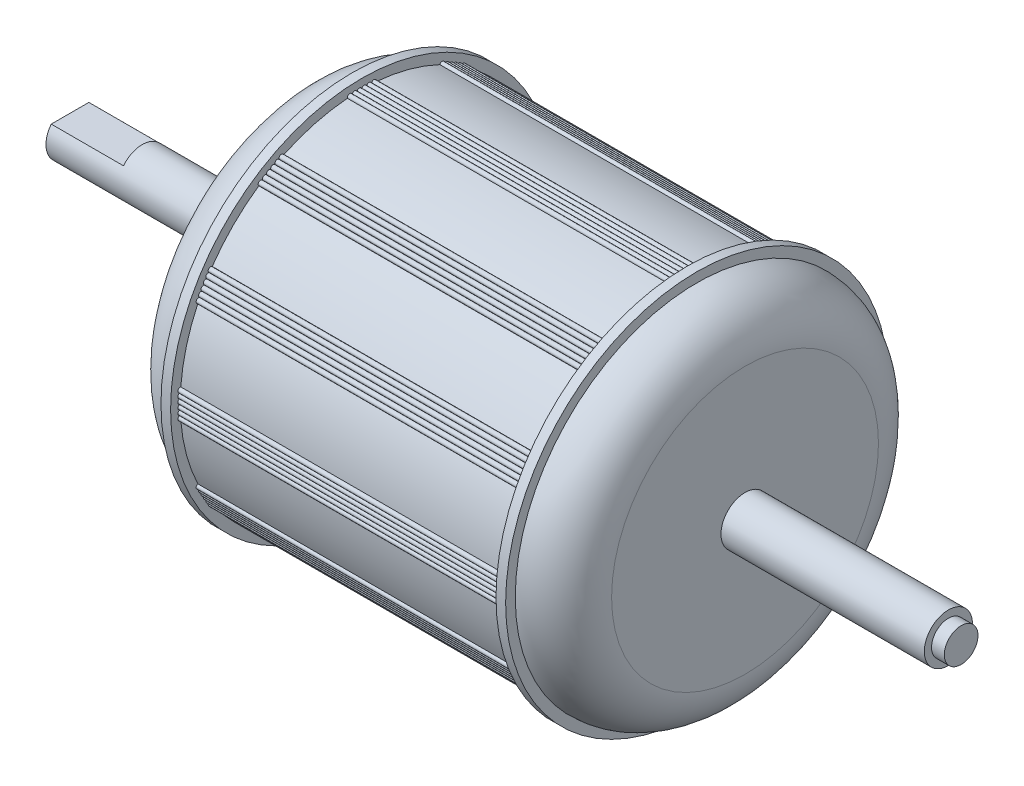
SolidWorks part; units mm, degrees
ref_plane "Front Plane" through (0, 0, 0) normal (0, 0, 1) x (1, 0, 0)
ref_plane "Top Plane" through (0, 0, 0) normal (0, 1, 0) x (1, 0, 0)
ref_plane "Right Plane" through (0, 0, 0) normal (1, 0, 0) x (0, 0, -1)
sketch "Sketch1" plane through (0, 0, 0) normal (0, 0, 1) x (1, 0, 0)
  line L0 (0, 0) -> (185.01, 0) construction
  line L1 (185.01, 0) -> (185.01, 3.5)
  line L2 (185.01, 3.5) -> (182.36, 3.5)
  line L3 (182.36, 3.5) -> (182.36, 5)
  line L4 (182.36, 5) -> (140.14, 5)
  line L5 (0, 0) -> (0, 5)
  line L6 (0, 5) -> (48.58, 5)
  line L7 (48.58, 5) -> (48.58, 27.705)
  line L8 (58.58, 37.705) -> (58.58, 39.705)
  line L9 (58.58, 39.705) -> (60.58, 39.705)
  line L10 (60.58, 39.705) -> (60.58, 37.71)
  line L11 (60.58, 37.71) -> (128.14, 37.71)
  line L13 (128.14, 39.705) -> (128.14, 37.71)
  line L14 (130.14, 39.705) -> (128.14, 39.705)
  line L15 (130.14, 37.705) -> (130.14, 39.705)
  line L16 (140.14, 5) -> (140.14, 27.705)
  line L17 (185.01, 0) -> (0, 0)
  arc A0 (48.58, 27.705) -> (58.58, 37.705) centre (58.58, 27.705) cw
  arc A1 (140.14, 27.705) -> (130.14, 37.705) centre (130.14, 27.705) ccw
  point P22 (94.36, 37.71)
  dimension "D6" = 10
  dimension "D1" = 185.01
  dimension "D2" = 7
  dimension "D3" = 2.65
  dimension "D4" = 10
  dimension "D5" = 48.58
  dimension "D7" = 79.41
  dimension "D8" = 2
  dimension "D9" = 37.71
  dimension "D10" = 12
  dimension "D11" = 91.56
  dimension "D12" = 67.56
revolve "Revolve1" add sketch "Sketch1" angle 360 about L17
sketch "Sketch2" plane through (0, 0, 0) normal (-1, 0, 0) x (0, 0, 1)
  line L0 (-3.905, 3.1227) -> (-3.905, 3.12)
  line L1 (-3.905, 3.12) -> (3.905, 3.12)
  line L2 (3.905, 3.12) -> (3.905, 3.1227)
  circle A0 centre (0, 0) radius 5 construction
  circle A1 centre (0, 0) radius 5 construction
  arc A2 (3.905, 3.1227) -> (-3.905, 3.1227) centre (0, 0) ccw
  point P4 (0, 3.12)
  point P9 (0, 5)
  dimension "D1" = 7.81
  dimension "D2" = 1.88
extrude "Cut-Extrude1" cut sketch "Sketch2" against normal blind 15
sketch "Sketch3" plane through (60.58, 0, 0) normal (1, 0, 0) x (0, 0, -1)
  line L0 (-3, 37.5905) -> (-3, 34.71)
  line L1 (3, 37.5905) -> (3, 34.71)
  line L2 (16.1972, 34.0543) -> (14.7569, 31.5597)
  line L3 (21.3933, 31.0543) -> (19.9531, 28.5597)
  line L4 (31.0543, 21.3933) -> (28.5597, 19.9531)
  line L5 (34.0543, 16.1972) -> (31.5597, 14.7569)
  line L6 (37.5905, 3) -> (34.71, 3)
  line L7 (37.5905, -3) -> (34.71, -3)
  line L8 (34.0543, -16.1972) -> (31.5597, -14.7569)
  line L9 (31.0543, -21.3933) -> (28.5597, -19.9531)
  line L10 (21.3933, -31.0543) -> (19.9531, -28.5597)
  line L11 (16.1972, -34.0543) -> (14.7569, -31.5597)
  line L12 (3, -37.5905) -> (3, -34.71)
  line L13 (-3, -37.5905) -> (-3, -34.71)
  line L14 (-16.1972, -34.0543) -> (-14.7569, -31.5597)
  line L15 (-21.3933, -31.0543) -> (-19.9531, -28.5597)
  line L16 (-31.0543, -21.3933) -> (-28.5597, -19.9531)
  line L17 (-34.0543, -16.1972) -> (-31.5597, -14.7569)
  line L18 (-37.5905, -3) -> (-34.71, -3)
  line L19 (-37.5905, 3) -> (-34.71, 3)
  line L20 (-34.0543, 16.1972) -> (-31.5597, 14.7569)
  line L21 (-31.0543, 21.3933) -> (-28.5597, 19.9531)
  line L22 (-21.3933, 31.0543) -> (-19.9531, 28.5597)
  line L23 (-16.1972, 34.0543) -> (-14.7569, 31.5597)
  circle A0 centre (0, 0) radius 37.71 construction
  arc A2 (3, 37.5905) -> (-3, 37.5905) centre (0, 0) ccw
  arc A3 (-3, 34.71) -> (3, 34.71) centre (0, 34.71) ccw
  arc A4 (21.3933, 31.0543) -> (16.1972, 34.0543) centre (0, 0) ccw
  arc A5 (14.7569, 31.5597) -> (19.9531, 28.5597) centre (17.355, 30.0597) ccw
  arc A6 (34.0543, 16.1972) -> (31.0543, 21.3933) centre (0, 0) ccw
  arc A7 (28.5597, 19.9531) -> (31.5597, 14.7569) centre (30.0597, 17.355) ccw
  arc A8 (37.5905, -3) -> (37.5905, 3) centre (0, 0) ccw
  arc A9 (34.71, 3) -> (34.71, -3) centre (34.71, 0) ccw
  arc A10 (31.0543, -21.3933) -> (34.0543, -16.1972) centre (0, 0) ccw
  arc A11 (31.5597, -14.7569) -> (28.5597, -19.9531) centre (30.0597, -17.355) ccw
  arc A12 (16.1972, -34.0543) -> (21.3933, -31.0543) centre (0, 0) ccw
  arc A13 (19.9531, -28.5597) -> (14.7569, -31.5597) centre (17.355, -30.0597) ccw
  arc A14 (-3, -37.5905) -> (3, -37.5905) centre (0, 0) ccw
  arc A15 (3, -34.71) -> (-3, -34.71) centre (0, -34.71) ccw
  arc A16 (-21.3933, -31.0543) -> (-16.1972, -34.0543) centre (0, 0) ccw
  arc A17 (-14.7569, -31.5597) -> (-19.9531, -28.5597) centre (-17.355, -30.0597) ccw
  arc A18 (-34.0543, -16.1972) -> (-31.0543, -21.3933) centre (0, 0) ccw
  arc A19 (-28.5597, -19.9531) -> (-31.5597, -14.7569) centre (-30.0597, -17.355) ccw
  arc A20 (-37.5905, 3) -> (-37.5905, -3) centre (0, 0) ccw
  arc A21 (-34.71, -3) -> (-34.71, 3) centre (-34.71, 0) ccw
  arc A22 (-31.0543, 21.3933) -> (-34.0543, 16.1972) centre (0, 0) ccw
  arc A23 (-31.5597, 14.7569) -> (-28.5597, 19.9531) centre (-30.0597, 17.355) ccw
  arc A24 (-16.1972, 34.0543) -> (-21.3933, 31.0543) centre (0, 0) ccw
  arc A25 (-19.9531, 28.5597) -> (-14.7569, 31.5597) centre (-17.355, 30.0597) ccw
  point P9 (0, 37.71)
  point P65 (0, 0)
  dimension "D2" = 34.71
  dimension "D1" = 6
  dimension "D3" = 12
extrude "Cut-Extrude2" cut sketch "Sketch3" along normal up to surface (67.56 mm away) up to face at (128.14, 0, -37.71)
sketch "Sketch4" plane through (60.58, 0, 0) normal (1, 0, 0) x (0, 0, -1)
  circle A0 centre (-2.5, 37.7) radius 0.5
  point P150 (0, 0)
  dimension "D1" = 1
  dimension "D3" = 2.5
extrude "Boss-Extrude10" add sketch "Sketch4" along normal up to next separate body
pattern_linear "LPattern3" count 6 spacing 1 along (0, 0, -1) of bodies 104
pattern_circular "CirPattern1" count 12 over 360 about axis through (0, 0, 0) along (1, 0, 0)
